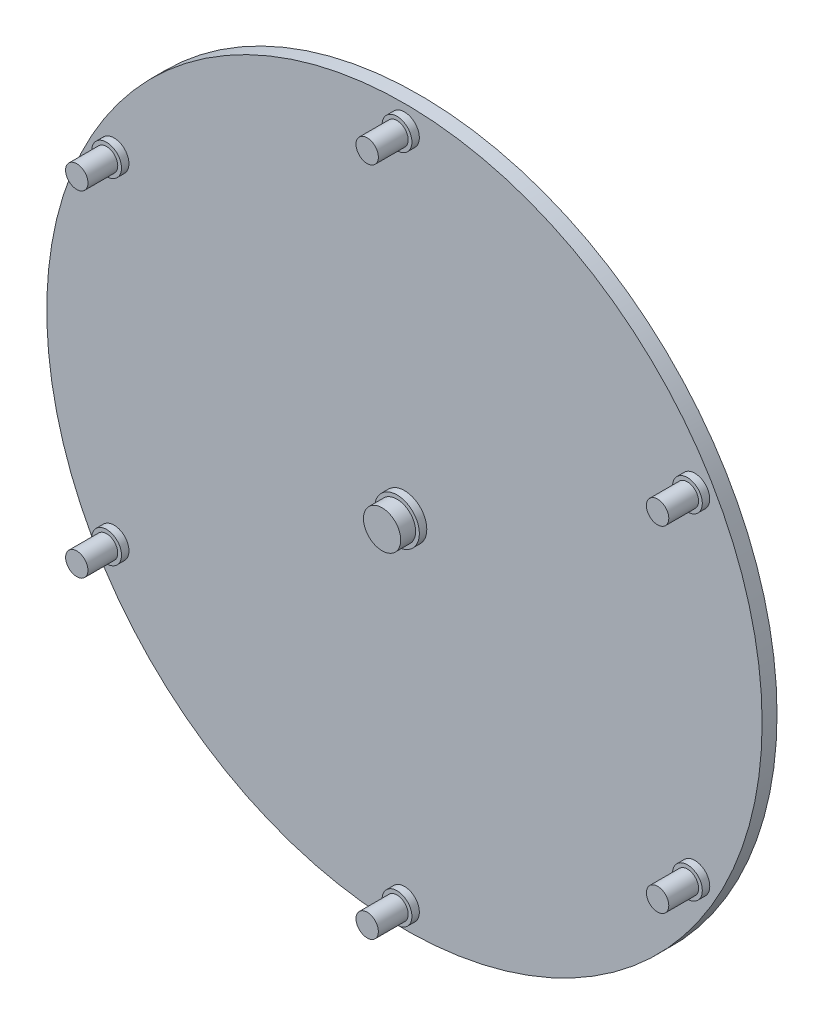
SolidWorks part; units mm, degrees
ref_plane "前视基准面" through (0, 0, 0) normal (0, 0, 1) x (1, 0, 0)
ref_plane "上视基准面" through (0, 0, 0) normal (0, 1, 0) x (1, 0, 0)
ref_plane "右视基准面" through (0, 0, 0) normal (1, 0, 0) x (0, 0, -1)
other "Configuration Table"
sketch "草图1" plane through (0, 0, 0) normal (0, 0, 1) x (1, 0, 0)
  circle A0 centre (0, 0) radius 96
  circle A1 centre (0, 90) radius 6 construction
extrude "凸台-拉伸1" add sketch "草图1" along normal blind 4
sketch "草图2" plane through (0, 0, 4) normal (0, 0, 1) x (1, 0, 0)
  circle A0 centre (0, 0) radius 5
  dimension "D1" = 10
extrude "凸台-拉伸2" add sketch "草图2" along normal blind 6
sketch "草图3" plane through (0, 0, 4) normal (0, 0, 1) x (1, 0, 0)
  circle A0 centre (0, 90) radius 3
  dimension "D1" = 6
  dimension "D2" = 90
extrude "凸台-拉伸3" add sketch "草图3" along normal blind 10
pattern_circular "阵列(圆周)1" count 6 over 360 about axis through (0, 0, 0) along (0, 0, 1) of "凸台-拉伸3"
sketch "草图4" plane through (0, 0, 4) normal (0, 0, 1) x (1, 0, 0)
  circle A3 centre (0, 0) radius 6
  circle A4 centre (0, 0) radius 6
  dimension "D1" = 1
extrude "凸台-拉伸4" add sketch "草图4" along normal blind 2
sketch "草图5" plane through (0, 0, 4) normal (0, 0, 1) x (1, 0, 0)
  circle A2 centre (0, 90) radius 4
  circle A3 centre (0, 90) radius 4
  dimension "D1" = 1
extrude "凸台-拉伸5" add sketch "草图5" along normal blind 2
pattern_circular "阵列(圆周)2" count 6 over 360 about axis through (0, 0, 0) along (0, 0, 1) of "凸台-拉伸5"
sketch "草图6" plane through (0, 0, 0) normal (0, 0, -1) x (-1, 0, 0)
  circle A0 centre (0, 0) radius 7
  dimension "D1" = 14
extrude "凸台-拉伸6" add sketch "草图6" along normal blind 8
sketch "草图7" plane through (0, 0, -8) normal (0, 0, -1) x (-1, 0, 0)
  circle A0 centre (0, 0) radius 5
  dimension "D1" = 10
extrude "拉伸-薄壁1" add sketch "草图7" along normal blind 15 thin thin type one direction reverse wall 2
